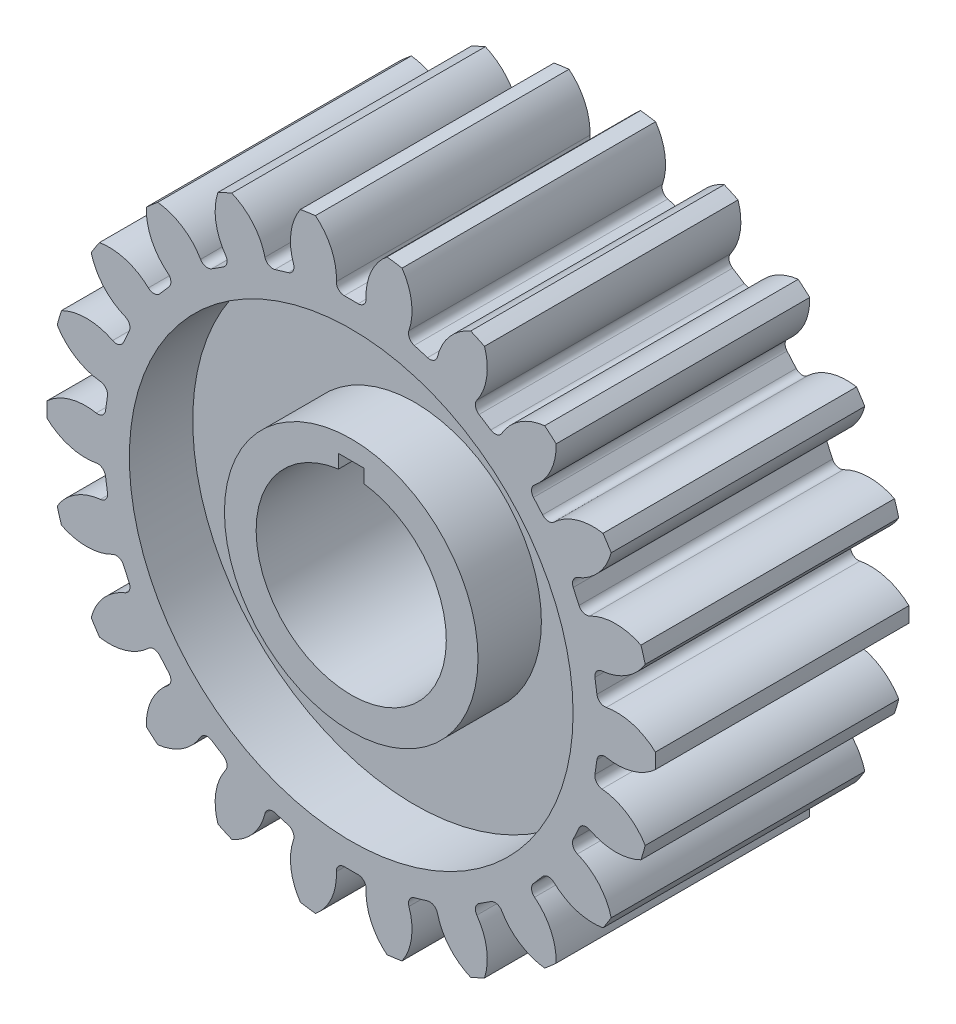
SolidWorks part; units mm, degrees
ref_plane "Front Plane" through (0, 0, 0) normal (0, 0, 1) x (1, 0, 0)
ref_plane "Top Plane" through (0, 0, 0) normal (0, 1, 0) x (1, 0, 0)
ref_plane "Right Plane" through (0, 0, 0) normal (1, 0, 0) x (0, 0, -1)
sketch "Sketch1" plane through (0, 0, 0) normal (0, 0, 1) x (1, 0, 0)
  circle A0 centre (0, 0) radius 24
  dimension "D1" = 48
extrude "Gear Profile" add sketch "Sketch1" along normal mid plane 20
sketch "Sketch2" plane through (0, 0, 10) normal (0, 0, 1) x (1, 0, 0)
  line L0 (-0.549, 19.5) -> (0.549, 19.5)
  line L1 (0, 25.9565) -> (0, 20.9874) construction
  arc A1 (1.1734, 20.1524) -> (2.8208, 23.8337) centre (5.669, 20.3498) cw
  circle A2 centre (0, 0) radius 24 construction
  arc A3 (-1.1734, 20.1524) -> (-2.8208, 23.8337) centre (-5.669, 20.3498) ccw
  arc A4 (0.549, 19.5) -> (1.1734, 20.1524) centre (0.549, 20.125) ccw
  circle A5 centre (0, 0) radius 24
  arc A6 (2.8208, 23.8337) -> (-2.8208, 23.8337) centre (0, 0) ccw
  arc A7 (-1.1734, 20.1524) -> (-0.549, 19.5) centre (-0.549, 20.125) ccw
  point P1 (0, 19.5)
  point P17 (1.25, 19.5)
  point P20 (-1.25, 19.5)
  dimension "D1" = 0.625
  dimension "D3" = 4.5
  dimension "D5" = 0
  dimension "D2" = 1.25
  dimension "D4" = 1.5708
extrude "Teeth profile" cut sketch "Sketch2" against normal through all
pattern_circular "Teeth  Profile Pattern" count 22 over 360 about axis through (0, 0, 0) along (0, 0, 1) of "Teeth profile"
sketch "Sketch3" plane through (0, 0, 10) normal (0, 0, 1) x (1, 0, 0)
  line L2 (-1, 7.433) -> (-1, 8.5)
  line L3 (-1, 8.5) -> (1, 8.5)
  line L4 (1, 7.433) -> (1, 8.5)
  arc A0 (-1, 7.433) -> (1, 7.433) centre (0, 0) ccw
  point P3 (0, 7.5)
  dimension "D1" = 15
  dimension "D2" = 2
extrude "Gear Bore" cut sketch "Sketch3" against normal through all
sketch "Sketch4" plane through (0, 0, 10) normal (0, 0, 1) x (1, 0, 0)
  circle A0 centre (0, 0) radius 10
  circle A1 centre (0, 0) radius 17.5
  dimension "D1" = 35
  dimension "D2" = 20
extrude "Weight reduction Pocket 1" cut sketch "Sketch4" against normal blind 5
mirror "Weight reduction Pocket 2" about plane through (0, 0, 0) normal (0, 0, 1) of "Weight reduction Pocket 1"
